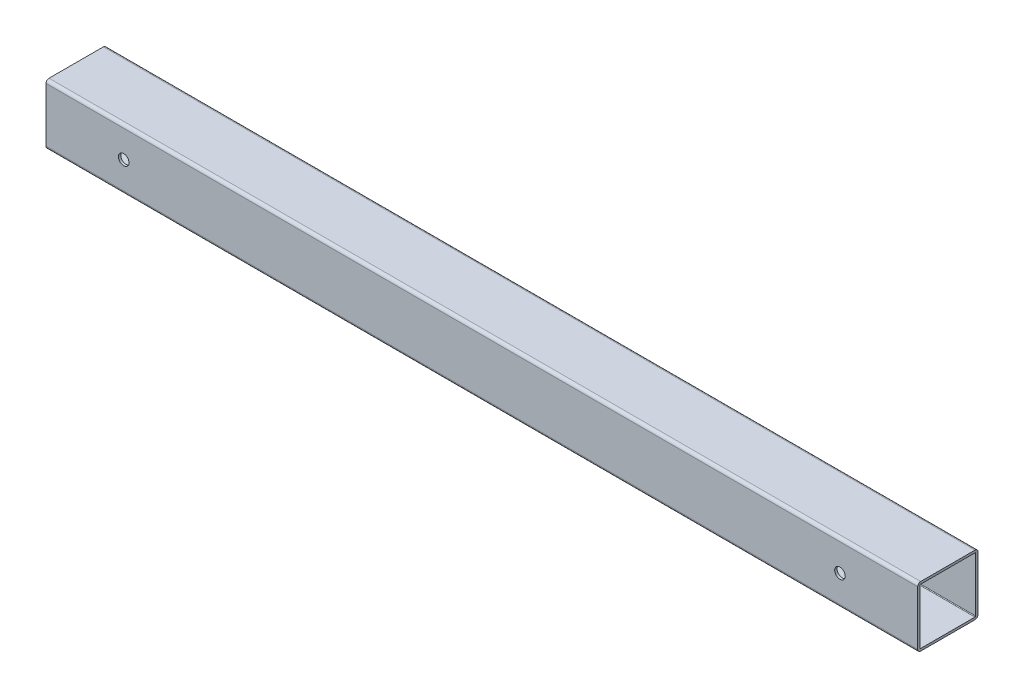
SolidWorks part; units mm, degrees
material "AISI 1020"
material "AISI 1020"
ref_plane "Plano frontal" through (0, 0, 0) normal (0, 0, 1) x (1, 0, 0)
ref_plane "Plano superior" through (0, 0, 0) normal (0, 1, 0) x (1, 0, 0)
ref_plane "Plano direito" through (0, 0, 0) normal (1, 0, 0) x (0, 0, -1)
other "Caixa delimitadora"
ref_plane "Default Plane" through (-289.0268, -20, -20) normal (0, 1, 0) x (1, 0, 0)
sketch "Esboço3" plane through (0, 0, 0) normal (0, 0, 1) x (1, 0, 0)
  line L0 (-289.0268, 0) -> (289.0268, 0)
  point P6 (0, 0)
other "Quadrado 40 X 40 X 1,55(1)"
ref_plane "Plano1" through (-289.0268, 0, 0) normal (1, 0, 0) x (0, 1, 0)
sketch "Esboço1" plane through (-289.0268, 0, 0) normal (1, 0, 0) x (0, 1, 0)
  line L0 (-18, -18.45) -> (18, -18.45)
  line L1 (-18.45, -18) -> (-18.45, 18)
  line L2 (18, 18.45) -> (-18, 18.45)
  line L3 (18.45, 18) -> (18.45, -18)
  line L4 (-18, -20) -> (18, -20)
  line L5 (-20, -18) -> (-20, 18)
  line L6 (18, 20) -> (-18, 20)
  line L7 (20, 18) -> (20, -18)
  line L8 (-20, 0) -> (-18.45, 0) construction
  line L9 (-18.45, 0) -> (18.45, 0) construction
  line L10 (18.45, 0) -> (20, 0) construction
  line L11 (0, 20) -> (0, 18.45) construction
  line L12 (0, 18.45) -> (0, -18.45) construction
  line L13 (0, -18.45) -> (0, -20) construction
  arc A0 (20, 18) -> (18, 20) centre (18, 18) ccw
  arc A1 (18, -20) -> (20, -18) centre (18, -18) ccw
  arc A2 (-20, -18) -> (-18, -20) centre (-18, -18) ccw
  arc A3 (-18, 20) -> (-20, 18) centre (-18, 18) ccw
  arc A4 (-18, 18.45) -> (-18.45, 18) centre (-18, 18) ccw
  arc A5 (18.45, 18) -> (18, 18.45) centre (18, 18) ccw
  arc A6 (18, -18.45) -> (18.45, -18) centre (18, -18) ccw
  arc A7 (-18.45, -18) -> (-18, -18.45) centre (-18, -18) ccw
  point P32 (0, 0)
  point P33 (0, 0)
  dimension "D1" = 2
  dimension "D2" = 40
  dimension "D3" = 40
  dimension "D4" = 1.55
sketch "Esboço4" plane through (0, 0, -20) normal (0, 0, -1) x (-1, 0, 0)
  line L0 (289.0268, 0) -> (-289.0268, 0) construction
  line L1 (0, 0) -> (0, -20) construction
  line L2 (-289.0268, -20) -> (289.0268, -20) construction
  line L5 (289.0268, -18) -> (289.0268, 18) construction
  circle A0 centre (-237.5, 0) radius 3.5
  circle A1 centre (237.5, 0) radius 3.5
  dimension "D1" = 7
  dimension "D2" = 51.5268
extrude "Corte-extrusão1" cut sketch "Esboço4" against normal through all both and the other way through all
equation "\"D3@Esboço1\"=\"D2@Esboço1\""
